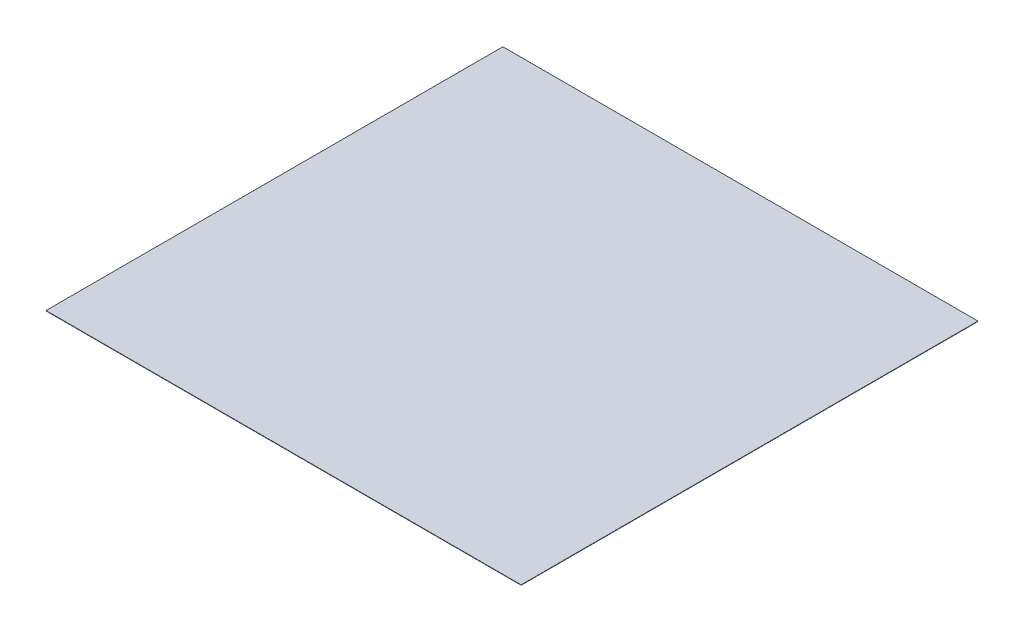
SolidWorks part; units mm, degrees
ref_plane "前视基准面" through (0, 0, 0) normal (0, 0, 1) x (1, 0, 0)
ref_plane "上视基准面" through (0, 0, 0) normal (0, 1, 0) x (1, 0, 0)
ref_plane "右视基准面" through (0, 0, 0) normal (1, 0, 0) x (0, 0, -1)
other "Configuration Table"
sketch "草图1" plane through (0, 0, 0) normal (0, 1, 0) x (1, 0, 0)
  line L1 (0, 0) -> (260, 0)
  line L2 (0, 0) -> (0, 250)
  line L3 (0, 250) -> (260, 250)
  line L4 (260, 0) -> (260, 250)
  dimension "D1" = 260
  dimension "D2" = 250
extrude "凸台-拉伸1" add sketch "草图1" along normal blind 0.2
